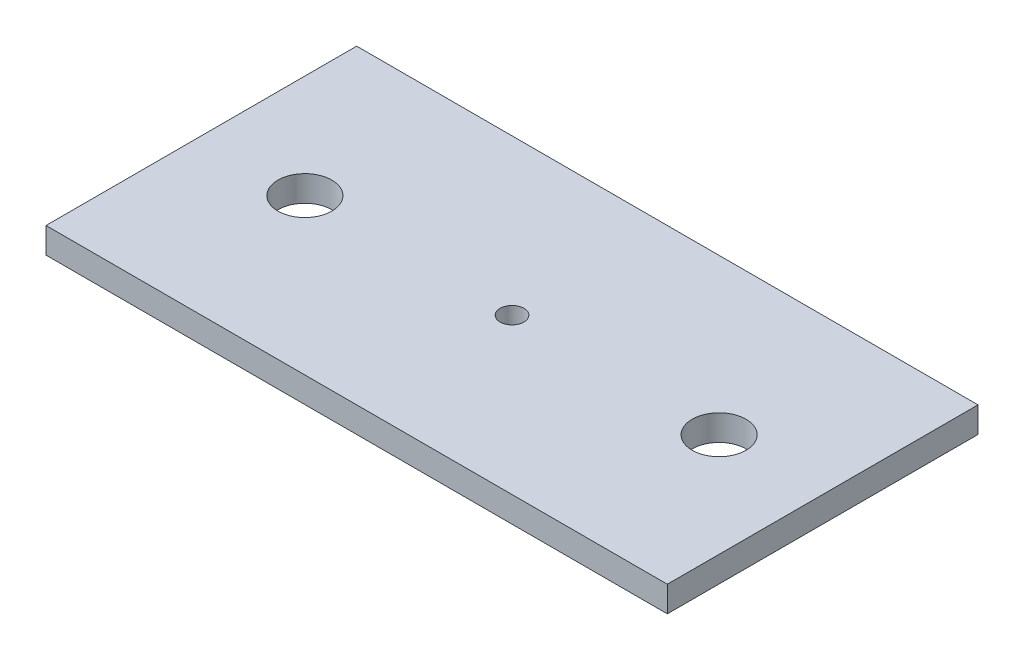
SolidWorks part; units mm, degrees
material "Acrylic (Medium-high impact)"
ref_plane "Front Plane" through (0, 0, 0) normal (0, 0, 1) x (1, 0, 0)
ref_plane "Top Plane" through (0, 0, 0) normal (0, 1, 0) x (1, 0, 0)
ref_plane "Right Plane" through (0, 0, 0) normal (1, 0, 0) x (0, 0, -1)
sketch "Sketch1" plane through (0, 0, 0) normal (0, 1, 0) x (1, 0, 0)
  line L1 (0, 0) -> (76.2, 0)
  line L2 (0, 0) -> (0, 38.1)
  line L3 (0, 38.1) -> (76.2, 38.1)
  line L4 (76.2, 0) -> (76.2, 38.1)
  dimension "D1" = 76.2
  dimension "D2" = 38.1
extrude "Boss-Extrude1" add sketch "Sketch1" along normal blind 3.1496
sketch "Sketch4" plane through (0, 3.1496, 0) normal (0, 1, 0) x (1, 0, 0)
  line L0 (76.2, 0) -> (76.2, 38.1) construction
  line L1 (0, 38.1) -> (0, 0) construction
  line L2 (76.2, 38.1) -> (0, 38.1) construction
  line L3 (0, 0) -> (76.2, 0) construction
  circle A0 centre (12.7, 19.05) radius 3.302
  circle A1 centre (63.5, 19.05) radius 3.302
  circle A2 centre (38.1, 19.05) radius 1.4605
  point P14 (38.1, 0)
  dimension "D1" = 6.604
  dimension "D2" = 6.604
  dimension "D3" = 50.8
  dimension "D4" = 12.7
  dimension "D5" = 12.7
  dimension "D6" = 19.05
  dimension "D7" = 2.921
  dimension "D8" = 19.05
  dimension "D9" = 38.1
extrude "Cut-Extrude2" cut sketch "Sketch4" against normal through all
